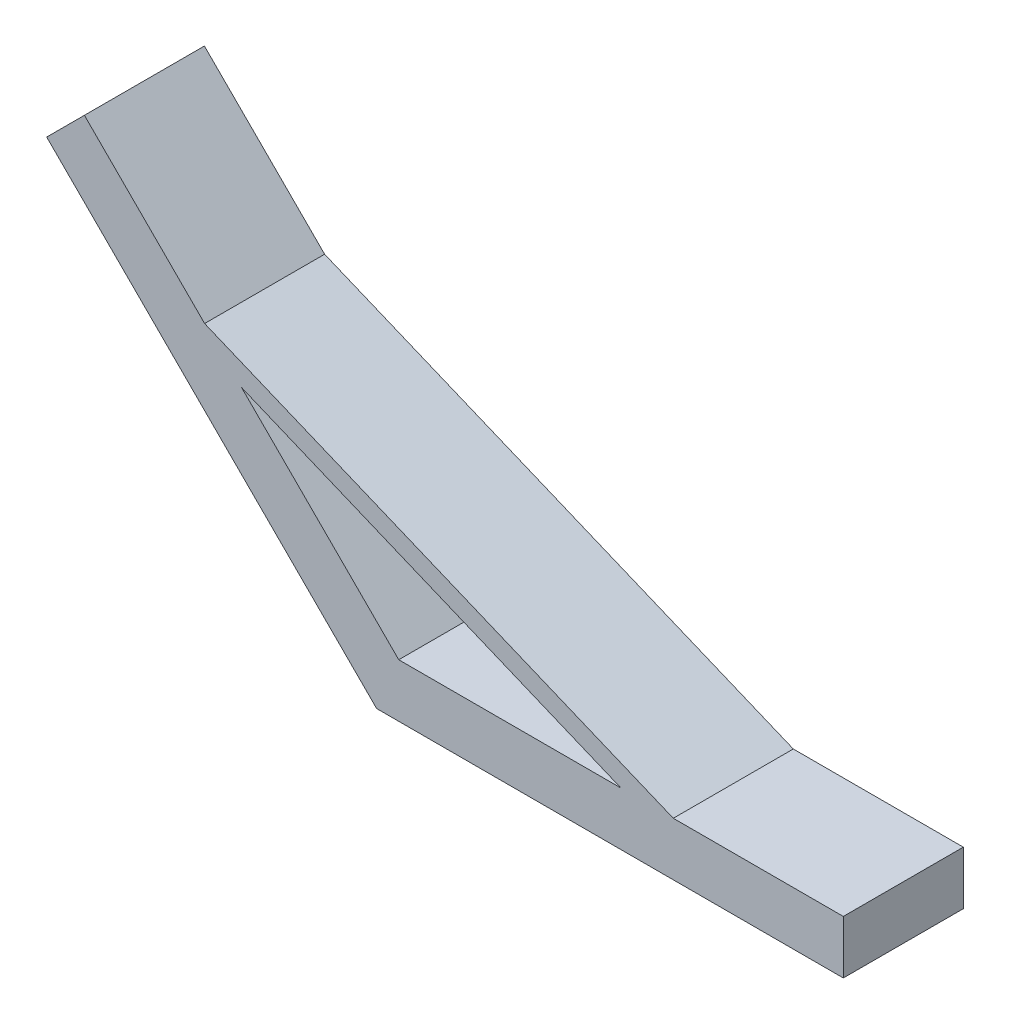
SolidWorks part; units mm, degrees
ref_plane "前视基准面" through (0, 0, 0) normal (0, 0, 1) x (1, 0, 0)
ref_plane "上视基准面" through (0, 0, 0) normal (0, 1, 0) x (1, 0, 0)
ref_plane "右视基准面" through (0, 0, 0) normal (1, 0, 0) x (0, 0, -1)
sketch "草图1" plane through (0, 0, 0) normal (0, 0, 1) x (1, 0, 0)
  line L0 (0, 0) -> (70, 0)
  line L1 (0, 0) -> (-49.4975, 49.4975)
  line L2 (-49.4975, 49.4975) -> (-43.8406, 55.1543)
  line L3 (-43.8406, 55.1543) -> (3.3137, 8)
  line L4 (3.3137, 8) -> (70, 8)
  line L5 (70, 8) -> (70, 0)
  line L6 (-20.2635, 31.5772) -> (36.6569, 8)
  line L7 (36.6569, 8) -> (44.4962, 8)
  line L8 (44.4962, 8) -> (-25.8067, 37.1204)
  line L9 (-25.8067, 37.1204) -> (-20.2635, 31.5772)
  dimension "D1" = 135
  dimension "D2" = 70
  dimension "D3" = 70
  dimension "D4" = 8
  dimension "D5" = 8
  dimension "D6" = 3
extrude "凸台-拉伸1" add sketch "草图1" along normal blind 18 contours L5 L4 L3 L2 L1 L0 | L4 L8 L3 L6
